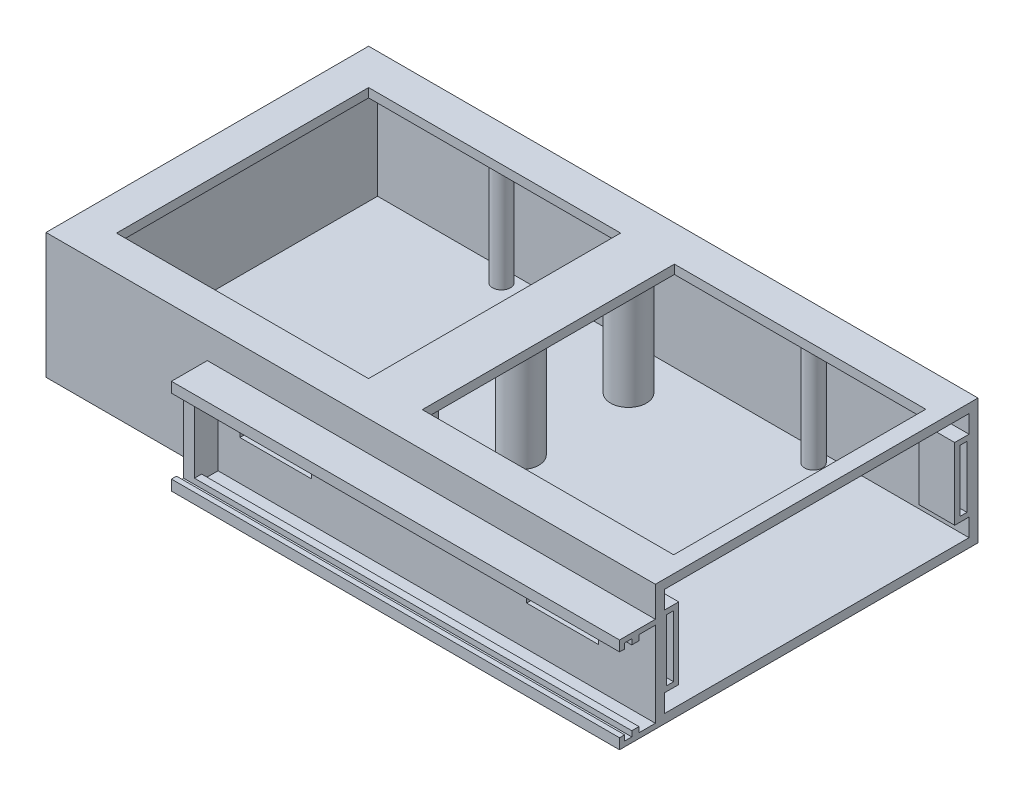
SolidWorks part; units mm, degrees
ref_plane "Спереди" through (0, 0, 0) normal (0, 0, 1) x (1, 0, 0)
ref_plane "Сверху" through (0, 0, 0) normal (0, 1, 0) x (1, 0, 0)
ref_plane "Справа" through (0, 0, 0) normal (1, 0, 0) x (0, 0, -1)
sketch "Эскиз1" plane through (0, 0, 0) normal (0, 1, 0) x (1, 0, 0)
  line L1 (-85, -45) -> (85, -45)
  line L2 (-85, -45) -> (-85, 45)
  line L3 (-85, 45) -> (85, 45)
  line L4 (85, -45) -> (85, 45)
  line L5 (-85, -45) -> (85, 45) construction
  line L6 (-85, 45) -> (85, -45) construction
  point P0 (0, 0)
extrude "Бобышка-Вытянуть1" add sketch "Эскиз1" along normal blind 35 contours L3 L4 L1 L2
sketch "Эскиз2" plane through (85, 0, 0) normal (1, 0, 0) x (0, 0, -1)
  line L0 (-1045, 17.5) -> (48955, 17.5) construction
  line L1 (-45, 35) -> (-45, 0) construction
  line L2 (0, -965) -> (0, 49035) construction
  line L3 (-45, 35) -> (45, 35) construction
  line L5 (-42.5, 2.5) -> (42.5, 2.5)
  line L6 (-42.5, 2.5) -> (-42.5, 32.5)
  line L7 (-42.5, 32.5) -> (42.5, 32.5)
  line L8 (42.5, 2.5) -> (42.5, 32.5)
  line L9 (-42.5, 2.5) -> (42.5, 32.5) construction
  line L10 (-42.5, 32.5) -> (42.5, 2.5) construction
  point P5 (-45, 17.5)
  point P6 (0, 17.5)
  point P10 (0, 35)
extrude "Вырез-Вытянуть1" cut sketch "Эскиз2" against normal blind 165
sketch "Эскиз3" plane through (0, 35, 0) normal (0, 1, 0) x (1, 0, 0)
  line L2 (10.2997, 35) -> (80.4294, 35)
  line L4 (-75, 35) -> (-4.7003, 35)
  line L5 (-75, 35) -> (-75, -35.327)
  line L6 (-75, -35.327) -> (-4.7003, -35.327)
  line L7 (-4.7003, 35) -> (-4.7003, -35.327)
  line L8 (10.2997, 35) -> (10.2997, -35.327)
  line L9 (10.2997, -35.327) -> (80.4294, -35.327)
  line L10 (80.4294, 35) -> (80.4294, -35.327)
extrude "Вырез-Вытянуть2" cut sketch "Эскиз3" against normal blind 10
sketch "Эскиз7" plane through (0, 0, 45) normal (0, 0, 1) x (1, 0, 0)
  line L0 (49.0894, 12.5) -> (49.0894, 22.5)
  line L2 (49.0894, 12.5) -> (69.0894, 12.5)
  line L4 (69.0894, 12.5) -> (69.0894, 22.5)
  line L6 (49.0894, 22.5) -> (69.0894, 22.5)
  line L7 (-30.9106, 12.5) -> (-10.9106, 12.5)
  line L8 (-30.9106, 12.5) -> (-30.9106, 22.5)
  line L9 (-30.9106, 22.5) -> (-10.9106, 22.5)
  line L10 (-10.9106, 12.5) -> (-10.9106, 22.5)
  point P8 (-20.9106, 17.5)
  dimension "D1" = 2
extrude "Вырез-Вытянуть3" cut sketch "Эскиз7" against normal blind 10
sketch "Эскиз8" plane through (0, 0, 0) normal (1, 0, 0) x (0, 0, -1)
  line L0 (-45, 26.5408) -> (-55, 26.5408)
  line L1 (-45, 35) -> (-45, 0) construction
  line L2 (-55, 26.5408) -> (-55, 0)
  line L3 (-55, 0) -> (-45, 0)
  line L4 (-45, 0) -> (-45, 26.5408)
extrude "Бобышка-Вытянуть2" add sketch "Эскиз8" along normal blind 85 and the other way blind 40
sketch "Эскиз9" plane through (85, 0, 0) normal (1, 0, 0) x (0, 0, -1)
  line L4 (-53.5858, 25.1266) -> (-45, 25.1266)
  line L6 (-53.5858, 1.4142) -> (-53.5858, 25.1266)
  line L7 (-53.5858, 1.4142) -> (-45, 1.4142)
  line L8 (-45, 1.4142) -> (-45, 25.1266)
extrude "Вырез-Вытянуть4" cut sketch "Эскиз9" against normal blind 122
sketch "Эскиз10" plane through (85, 0, 0) normal (1, 0, 0) x (0, 0, -1)
  line L1 (-53.5858, 25.1266) -> (-53.5858, 1.4142) construction
  line L3 (-53.5858, 2.9142) -> (-57.1914, 2.9142)
  line L4 (-57.1914, 2.9142) -> (-57.1914, 23.7109)
  line L5 (-57.1914, 23.7109) -> (-53.5858, 23.6301)
  line L6 (-53.5858, 2.9142) -> (-53.5858, 23.6301)
extrude "Вырез-Вытянуть5" cut sketch "Эскиз10" against normal blind 122
sketch "Эскиз11" plane through (85, 0, 0) normal (1, 0, 0) x (0, 0, -1)
  line L1 (-45, 25.1266) -> (-53.5858, 25.1266) construction
  line L2 (-51.5858, 25.1266) -> (-51.5858, 23.6301)
  line L3 (-51.5858, 23.6301) -> (-49.5858, 23.6301)
  line L4 (-49.5858, 23.6301) -> (-49.5858, 25.1266)
  line L5 (-49.5858, 25.1266) -> (-51.5858, 25.1266)
  line L6 (-51.5858, 1.4142) -> (-51.5858, 2.9142)
  line L7 (-53.5858, 1.4142) -> (-45, 1.4142) construction
  line L8 (-51.5858, 2.9142) -> (-49.5858, 2.9142)
  line L9 (-49.5858, 2.9142) -> (-49.5858, 1.4142)
  line L10 (-49.5858, 1.4142) -> (-51.5858, 1.4142)
extrude "Бобышка-Вытянуть3" add sketch "Эскиз11" against normal blind 122
sketch "Эскиз13" plane through (85, 0, 0) normal (1, 0, 0) x (0, 0, -1)
  line L0 (38.5, 7.5) -> (42.5, 7.5)
  line L1 (-42.5, 32.5) -> (-42.5, 2.5) construction
  line L2 (42.5, 7.5) -> (42.5, 27.5)
  line L3 (-42.5, 32.5) -> (-42.5, 2.5) construction
  line L4 (-42.5, 27.5) -> (-42.5, 7.5)
  line L5 (-42.5, 7.5) -> (-38.5, 7.5)
  line L6 (-38.5, 7.5) -> (-38.5, 27.5)
  line L7 (-38.5, 27.5) -> (-42.5, 27.5)
  line L8 (42.5, 27.5) -> (38.5, 27.5)
  line L9 (38.5, 27.5) -> (38.5, 7.5)
  dimension "D1" = 2
extrude "Бобышка-Вытянуть4" add sketch "Эскиз13" against normal blind 10
sketch "Эскиз14" plane through (85, 0, 0) normal (1, 0, 0) x (0, 0, -1)
  line L4 (-39.9142, 26.0858) -> (-41.9142, 26.0858)
  line L5 (39.9142, 26.0858) -> (41.9142, 26.0858)
  line L8 (-39.9142, 8.9142) -> (-39.9142, 26.0858)
  line L9 (39.9142, 8.9142) -> (39.9142, 26.0858)
  line L10 (-39.9142, 8.9142) -> (-41.9142, 8.9142)
  line L11 (39.9142, 8.9142) -> (41.9142, 8.9142)
  line L12 (-41.9142, 8.9142) -> (-41.9142, 26.0858)
  line L13 (41.9142, 8.9142) -> (41.9142, 26.0858)
extrude "Вырез-Вытянуть6" cut sketch "Эскиз14" against normal blind 5
sketch "Эскиз15" plane through (-37, 0, 0) normal (1, 0, 0) x (0, 0, -1)
  line L0 (-55, 23.6618) -> (-53.5858, 23.6301)
  line L1 (-53.5858, 23.6301) -> (-53.5858, 25.1266)
  line L2 (-53.5858, 25.1266) -> (-51.5858, 25.1266)
  line L3 (-51.5858, 25.1266) -> (-51.5858, 1.4142)
  line L4 (-51.5858, 1.4142) -> (-53.5858, 1.4142)
  line L5 (-53.5858, 1.4142) -> (-53.5858, 2.9142)
  line L6 (-53.5858, 2.9142) -> (-55, 2.9142)
  line L7 (-55, 2.9142) -> (-57.0353, 2.9142)
  line L8 (-57.0353, 2.9142) -> (-57.0353, 23.6459)
  line L9 (-57.0353, 23.6459) -> (-55, 23.6618)
extrude "Вырез-Вытянуть7" cut sketch "Эскиз15" against normal blind 5 and the other way through all
sketch "Эскиз16" plane through (0, 2.5, 0) normal (0, 1, 0) x (1, 0, 0)
  line L0 (2.5, -957.5) -> (2.5, 49042.5) construction
  line L1 (-80, 42.5) -> (85, 42.5) construction
  line L2 (-41.8212, -957.5) -> (-41.8212, 49042.5) construction
  line L3 (45.2264, -957.5) -> (45.2264, 49042.5) construction
  circle A0 centre (-41.8212, 38.9123) radius 2.5
  circle A1 centre (-41.8212, -38.9798) radius 2.5
  circle A2 centre (2.5, 0) radius 5
  circle A3 centre (45.2264, 38.9123) radius 2.5
  circle A4 centre (45.2264, -39.334) radius 2.5
  circle A5 centre (2.5, 30) radius 5
  circle A6 centre (2.5, 0) radius 5
  circle A7 centre (2.5, -30) radius 5
  point P5 (2.5, 42.5)
  dimension "D1" = 2
  dimension "D2" = 2
extrude "Бобышка-Вытянуть5" add sketch "Эскиз16" along normal blind 32 contours A0 | A1 | A2 | A4 | A7 | A5 | A3
